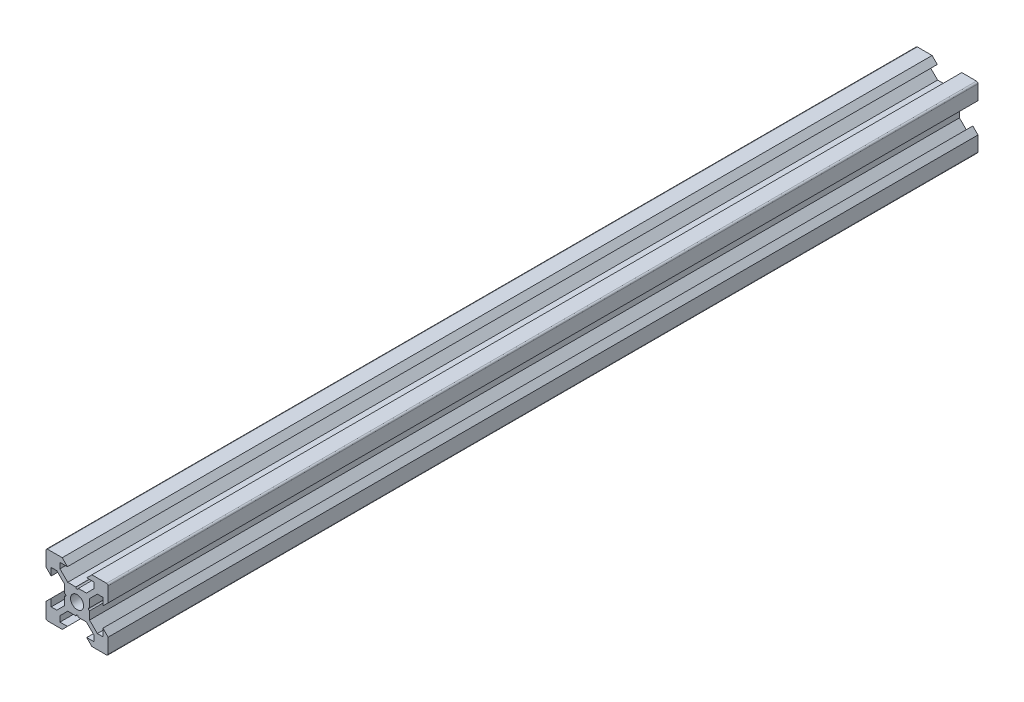
SolidWorks part; units mm, degrees
ref_plane "Front Plane" through (0, 0, 0) normal (0, 0, 1) x (1, 0, 0)
ref_plane "Top Plane" through (0, 0, 0) normal (0, 1, 0) x (1, 0, 0)
ref_plane "Right Plane" through (0, 0, 0) normal (1, 0, 0) x (0, 0, -1)
sketch "Sketch1" plane through (0, 0, 0) normal (0, 0, 1) x (1, 0, 0)
  line L0 (0, 11.7715) -> (0, -11.0375) construction
  line L1 (-10, 10) -> (10, 10) construction
  line L2 (-10, 10) -> (-10, -10) construction
  line L3 (-10, -10) -> (10, -10) construction
  line L4 (10, 10) -> (10, -10) construction
  line L5 (-10, 10) -> (10, -10) construction
  line L6 (-10, -10) -> (10, 10) construction
  line L7 (-5.5, 5.5) -> (5.5, 5.5) construction
  line L8 (-5.5, 5.5) -> (-5.5, -5.5) construction
  line L9 (-5.5, -5.5) -> (5.5, -5.5) construction
  line L10 (5.5, 5.5) -> (5.5, -5.5) construction
  line L11 (-5.5, 5.5) -> (5.5, -5.5) construction
  line L12 (-5.5, -5.5) -> (5.5, 5.5) construction
  line L13 (-10, 10) -> (-4.775, 10)
  line L14 (-4.775, 10) -> (-3.1, 8.325)
  line L15 (-3.1, 8.325) -> (-5.5, 8.325)
  line L16 (-5.5, 8.325) -> (-5.5, 6.525)
  line L17 (-5.5, 6.525) -> (-3, 4.025)
  line L18 (-3, 4.025) -> (3, 4.025)
  line L19 (-2.8044, 0) -> (3.0922, 0) construction
  line L20 (5.5, 6.525) -> (3, 4.025)
  line L21 (5.5, 8.325) -> (5.5, 6.525)
  line L22 (3.1, 8.325) -> (5.5, 8.325)
  line L23 (4.775, 10) -> (3.1, 8.325)
  line L24 (10, 10) -> (4.775, 10)
  line L25 (10, -10) -> (4.775, -10)
  line L26 (4.775, -10) -> (3.1, -8.325)
  line L27 (3.1, -8.325) -> (5.5, -8.325)
  line L28 (5.5, -8.325) -> (5.5, -6.525)
  line L29 (5.5, -6.525) -> (3, -4.025)
  line L30 (-3.1, -8.325) -> (-5.5, -8.325)
  line L31 (-3, -4.025) -> (3, -4.025)
  line L32 (-5.5, -6.525) -> (-3, -4.025)
  line L33 (-5.5, -8.325) -> (-5.5, -6.525)
  line L34 (-4.775, -10) -> (-3.1, -8.325)
  line L35 (-10, -10) -> (-4.775, -10)
  line L36 (-4.025, 3) -> (-4.025, -3)
  line L37 (-6.525, 5.5) -> (-4.025, 3)
  line L38 (-8.325, 5.5) -> (-6.525, 5.5)
  line L39 (-8.325, 3.1) -> (-8.325, 5.5)
  line L40 (-10, 4.775) -> (-8.325, 3.1)
  line L41 (-10, 10) -> (-10, 4.775)
  line L42 (-10, -10) -> (-10, -4.775)
  line L43 (-10, -4.775) -> (-8.325, -3.1)
  line L44 (-8.325, -3.1) -> (-8.325, -5.5)
  line L45 (-8.325, -5.5) -> (-6.525, -5.5)
  line L46 (-6.525, -5.5) -> (-4.025, -3)
  line L47 (10, -10) -> (10, -4.775)
  line L48 (10, -4.775) -> (8.325, -3.1)
  line L49 (8.325, -3.1) -> (8.325, -5.5)
  line L50 (8.325, -5.5) -> (6.525, -5.5)
  line L51 (6.525, -5.5) -> (4.025, -3)
  line L52 (4.025, 3) -> (4.025, -3)
  line L53 (6.525, 5.5) -> (4.025, 3)
  line L54 (8.325, 5.5) -> (6.525, 5.5)
  line L55 (8.325, 3.1) -> (8.325, 5.5)
  line L56 (10, 4.775) -> (8.325, 3.1)
  line L57 (10, 10) -> (10, 4.775)
  circle A0 centre (0, 0) radius 2.1
  point P0 (0, 0)
  point P6 (0, 0)
  point P23 (0, 4.025)
  dimension "D3" = 4.2
  dimension "D1" = 20
  dimension "D2" = 20
  dimension "D4" = 45
  dimension "D5" = 45
  dimension "D6" = 9.55
  dimension "D7" = 6.2
  dimension "D8" = 11
  dimension "D9" = 1.675
  dimension "D10" = 4.3
  dimension "D11" = 9.55
  dimension "D12" = 6.2
  dimension "D13" = 1.675
  dimension "D14" = 4.3
  dimension "D15" = 1.8
  dimension "D16" = 1.8
  dimension "D17" = 45
extrude "Boss-Extrude1" add sketch "Sketch1" along normal blind 280
fillet "Fillet1" radius 0.5 4 edges at (-10, -10, 140) (10, -10, 140) (10, 10, 140) (-10, 10, 140)
sketch "Sketch2" plane through (0, 0, 280) normal (0, 0, 1) x (1, 0, 0)
  line L0 (-0.8203, 0) -> (1.3478, 0) construction
  line L1 (0, 1.2196) -> (0, -1.1398) construction
  line L44 (-10, -4.775) -> (-10, -9.5)
  line L45 (-9.5, -10) -> (-4.775, -10)
  line L46 (-4.775, -10) -> (-3.1, -8.325)
  line L47 (-3.1, -8.325) -> (-5.5, -8.325)
  line L48 (-5.5, -8.325) -> (-5.5, -6.525)
  line L49 (-5.5, -6.525) -> (-3, -4.025)
  line L50 (-3, -4.025) -> (3, -4.025)
  line L51 (3, -4.025) -> (5.5, -6.525)
  line L52 (5.5, -6.525) -> (5.5, -8.325)
  line L53 (5.5, -8.325) -> (3.1, -8.325)
  line L54 (3.1, -8.325) -> (4.775, -10)
  line L55 (4.775, -10) -> (9.5, -10)
  line L56 (10, -9.5) -> (10, -4.775)
  line L57 (10, -4.775) -> (8.325, -3.1)
  line L58 (8.325, -3.1) -> (8.325, -5.5)
  line L59 (8.325, -5.5) -> (6.525, -5.5)
  line L60 (6.525, -5.5) -> (4.025, -3)
  line L61 (4.025, -3) -> (4.025, 3)
  line L62 (4.025, 3) -> (6.525, 5.5)
  line L63 (6.525, 5.5) -> (8.325, 5.5)
  line L64 (8.325, 5.5) -> (8.325, 3.1)
  line L65 (8.325, 3.1) -> (10, 4.775)
  line L66 (10, 4.775) -> (10, 9.5)
  line L67 (9.5, 10) -> (4.775, 10)
  line L68 (4.775, 10) -> (3.1, 8.325)
  line L69 (3.1, 8.325) -> (5.5, 8.325)
  line L70 (5.5, 8.325) -> (5.5, 6.525)
  line L71 (5.5, 6.525) -> (3, 4.025)
  line L72 (3, 4.025) -> (-3, 4.025)
  line L73 (-3, 4.025) -> (-5.5, 6.525)
  line L74 (-5.5, 6.525) -> (-5.5, 8.325)
  line L75 (-5.5, 8.325) -> (-3.1, 8.325)
  line L76 (-3.1, 8.325) -> (-4.775, 10)
  line L77 (-4.775, 10) -> (-9.5, 10)
  line L78 (-10, 9.5) -> (-10, 4.775)
  line L79 (-10, 4.775) -> (-8.325, 3.1)
  line L80 (-8.325, 3.1) -> (-8.325, 5.5)
  line L81 (-8.325, 5.5) -> (-6.525, 5.5)
  line L82 (-6.525, 5.5) -> (-4.025, 3)
  line L83 (-4.025, 3) -> (-4.025, -3)
  line L84 (-4.025, -3) -> (-6.525, -5.5)
  line L85 (-6.525, -5.5) -> (-8.325, -5.5)
  line L86 (-8.325, -5.5) -> (-8.325, -3.1)
  line L87 (-8.325, -3.1) -> (-10, -4.775)
  line L88 (-10, -4.775) -> (-10, -9.5)
  line L89 (-9.5, -10) -> (-4.775, -10)
  line L90 (-4.775, -10) -> (-3.1, -8.325)
  line L91 (-3.1, -8.325) -> (-5.5, -8.325)
  line L92 (-5.5, -8.325) -> (-5.5, -6.525)
  line L93 (-5.5, -6.525) -> (-3, -4.025)
  line L94 (-3, -4.025) -> (3, -4.025)
  line L95 (3, -4.025) -> (5.5, -6.525)
  line L96 (5.5, -6.525) -> (5.5, -8.325)
  line L97 (5.5, -8.325) -> (3.1, -8.325)
  line L98 (3.1, -8.325) -> (4.775, -10)
  line L99 (4.775, -10) -> (9.5, -10)
  line L100 (10, -9.5) -> (10, -4.775)
  line L101 (10, -4.775) -> (8.325, -3.1)
  line L102 (8.325, -3.1) -> (8.325, -5.5)
  line L103 (8.325, -5.5) -> (6.525, -5.5)
  line L104 (6.525, -5.5) -> (4.025, -3)
  line L105 (4.025, -3) -> (4.025, 3)
  line L106 (4.025, 3) -> (6.525, 5.5)
  line L107 (6.525, 5.5) -> (8.325, 5.5)
  line L108 (8.325, 5.5) -> (8.325, 3.1)
  line L109 (8.325, 3.1) -> (10, 4.775)
  line L110 (10, 4.775) -> (10, 9.5)
  line L111 (9.5, 10) -> (4.775, 10)
  line L112 (4.775, 10) -> (3.1, 8.325)
  line L113 (3.1, 8.325) -> (5.5, 8.325)
  line L114 (5.5, 8.325) -> (5.5, 6.525)
  line L115 (5.5, 6.525) -> (3, 4.025)
  line L116 (3, 4.025) -> (-3, 4.025)
  line L117 (-3, 4.025) -> (-5.5, 6.525)
  line L118 (-5.5, 6.525) -> (-5.5, 8.325)
  line L119 (-5.5, 8.325) -> (-3.1, 8.325)
  line L120 (-3.1, 8.325) -> (-4.775, 10)
  line L121 (-4.775, 10) -> (-9.5, 10)
  line L122 (-10, 9.5) -> (-10, 4.775)
  line L123 (-10, 4.775) -> (-8.325, 3.1)
  line L124 (-8.325, 3.1) -> (-8.325, 5.5)
  line L125 (-8.325, 5.5) -> (-6.525, 5.5)
  line L126 (-6.525, 5.5) -> (-4.025, 3)
  line L127 (-4.025, 3) -> (-4.025, -3)
  line L128 (-4.025, -3) -> (-6.525, -5.5)
  line L129 (-6.525, -5.5) -> (-8.325, -5.5)
  line L130 (-8.325, -5.5) -> (-8.325, -3.1)
  line L131 (-8.325, -3.1) -> (-10, -4.775)
  circle A0 centre (-4.025, 0) radius 0.4
  circle A1 centre (4.025, 0) radius 0.4
  circle A2 centre (0, 4.025) radius 0.4
  circle A3 centre (0, -4.025) radius 0.4
  arc A4 (-10, -9.5) -> (-9.5, -10) centre (-9.5, -9.5) ccw
  arc A5 (9.5, -10) -> (10, -9.5) centre (9.5, -9.5) ccw
  arc A6 (10, 9.5) -> (9.5, 10) centre (9.5, 9.5) ccw
  arc A7 (-9.5, 10) -> (-10, 9.5) centre (-9.5, 9.5) ccw
  arc A8 (-10, -9.5) -> (-9.5, -10) centre (-9.5, -9.5) ccw
  arc A9 (9.5, -10) -> (10, -9.5) centre (9.5, -9.5) ccw
  arc A10 (10, 9.5) -> (9.5, 10) centre (9.5, 9.5) ccw
  arc A11 (-9.5, 10) -> (-10, 9.5) centre (-9.5, 9.5) ccw
  dimension "D2" = 0.8
  dimension "D3" = 0.8
  dimension "D1" = 0
extrude "Cut-Extrude1" cut sketch "Sketch2" against normal through all contours L127 A0 | L116 A2 | A1 L105 | A3 L94
